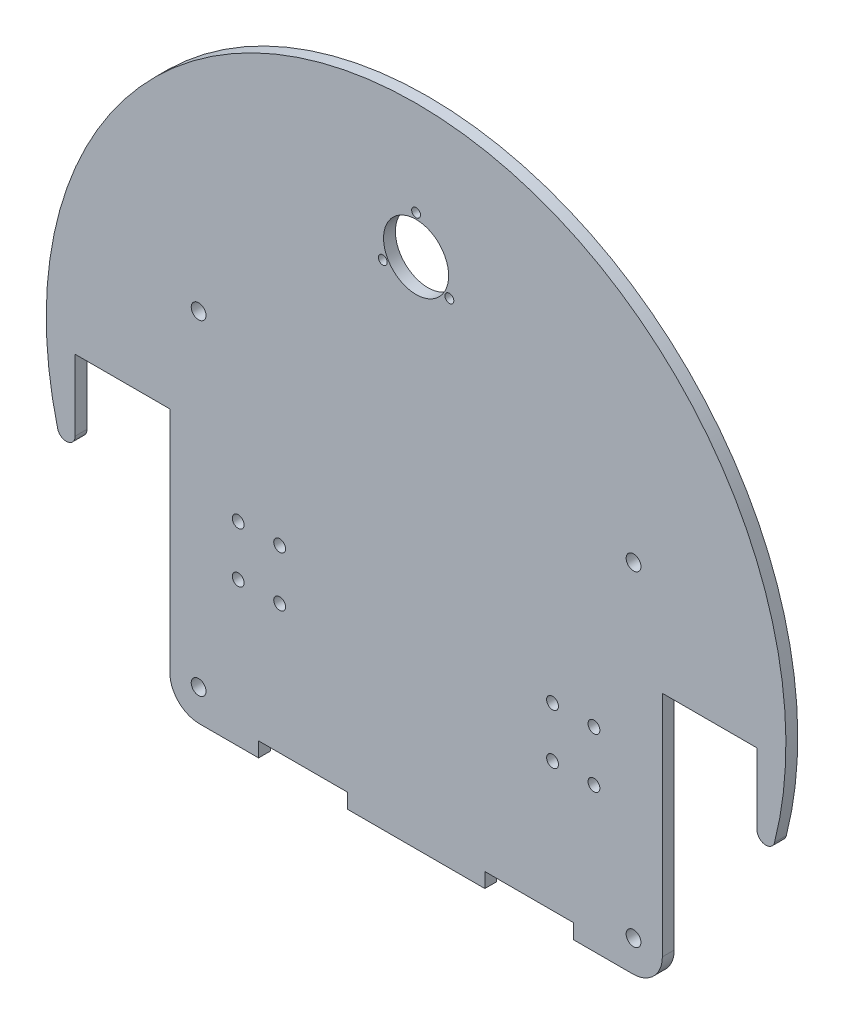
SolidWorks part; units mm, degrees
ref_plane "Front Plane" through (0, 0, 0) normal (0, 0, 1) x (1, 0, 0)
ref_plane "Top Plane" through (0, 0, 0) normal (0, 1, 0) x (1, 0, 0)
ref_plane "Right Plane" through (0, 0, 0) normal (1, 0, 0) x (0, 0, -1)
sketch "Sketch1" plane through (0, 0, 0) normal (0, 0, 1) x (1, 0, 0)
  line L0 (-115.2338, -48.4373) -> (-115.2338, -6.094)
  line L1 (-115.2338, -6.094) -> (-83.2338, -6.094)
  line L2 (-83.2338, -6.094) -> (-83.2338, -93.2584)
  line L3 (0, 125) -> (0, -125) construction
  line L4 (115.2338, -48.4373) -> (115.2338, -6.094)
  line L5 (115.2338, -6.094) -> (83.2338, -6.094)
  line L6 (83.2338, -6.094) -> (83.2338, -93.2584)
  arc A0 (-83.2338, -93.2584) -> (83.2338, -93.2584) centre (0, 0) ccw
  circle A1 centre (0, 80) radius 11
  arc A2 (115.2338, -48.4373) -> (-115.2338, -48.4373) centre (0, 0) ccw
  dimension "D1" = 250
  dimension "D2" = 22
  dimension "D3" = 80
  dimension "D4" = 32
extrude "Boss-Extrude1" add sketch "Sketch1" along normal blind 4
sketch "Sketch2" plane through (0, 0, 4) normal (0, 0, 1) x (1, 0, 0)
  circle A0 centre (0, 92.9904) radius 1.5
  circle A1 centre (11.25, 73.5048) radius 1.5
  circle A2 centre (-11.25, 73.5048) radius 1.5
  dimension "D1" = 3
extrude "Cut-Extrude1" cut sketch "Sketch2" against normal blind 10
sketch "Sketch3" plane through (0, 0, 4) normal (0, 0, 1) x (1, 0, 0)
  line L0 (-83.2338, -93.2584) -> (83.2338, -93.2584)
  arc A0 (-83.2338, -93.2584) -> (83.2338, -93.2584) centre (0, 0) ccw construction
  arc A1 (-83.2338, -93.2584) -> (83.2338, -93.2584) centre (0, 0) ccw
extrude "Cut-Extrude2" cut sketch "Sketch3" against normal blind 10
fillet "Fillet1" radius 10 2 edges at (-83.2338, -93.2584, 2) (83.2338, -93.2584, 2)
fillet "Fillet3" radius 3 2 edges at (115.2338, -48.4373, 2) (-115.2338, -48.4373, 2)
sketch "Sketch5" plane through (0, 0, 4) normal (0, 0, 1) x (1, 0, 0)
  line L0 (73.2338, -93.2584) -> (-73.2338, -93.2584) construction
  line L1 (53.2338, -93.2584) -> (23.2338, -93.2584)
  line L2 (53.2338, -93.2584) -> (53.2338, -88.2584)
  line L3 (53.2338, -88.2584) -> (23.2338, -88.2584)
  line L4 (23.2338, -93.2584) -> (23.2338, -88.2584)
  line L5 (83.2338, -83.2584) -> (83.2338, -6.094) construction
  line L6 (0, 0) -> (0, -93.2584) construction
  line L7 (-23.2338, -93.2584) -> (-23.2338, -88.2584)
  line L8 (-53.2338, -88.2584) -> (-23.2338, -88.2584)
  line L9 (-53.2338, -93.2584) -> (-53.2338, -88.2584)
  line L10 (-53.2338, -93.2584) -> (-23.2338, -93.2584)
  dimension "D1" = 30
  dimension "D2" = 5
  dimension "D3" = 30
extrude "Cut-Extrude4" cut sketch "Sketch5" against normal blind 10
sketch "Sketch6" plane through (0, 0, 4) normal (0, 0, 1) x (1, 0, 0)
  circle A0 centre (-73.5, -82.6455) radius 2.5
  circle A1 centre (73.5, -82.6455) radius 2.5
  circle A2 centre (73.5, 27.3545) radius 2.5
  circle A3 centre (-73.5, 27.3545) radius 2.5
  dimension "D1" = 5
extrude "Cut-Extrude5" cut sketch "Sketch6" against normal through all
sketch "Sketch7" plane through (0, 0, 4) normal (0, 0, 1) x (1, 0, 0)
  line L0 (-115.2338, -30.0794) -> (-115.2338, 48.4373)
  arc A0 (121.1412, -30.819) -> (-121.1412, -30.819) centre (0, 0) ccw construction
  arc A1 (-121.1412, -30.819) -> (-115.2338, -30.0794) centre (-118.2338, -30.0794) ccw construction
  arc A2 (-115.2338, 48.4373) -> (-121.1412, -30.819) centre (0, 0) ccw
  arc A3 (-121.1412, -30.819) -> (-115.2338, -30.0794) centre (-118.2338, -30.0794) ccw
extrude "Cut-Extrude6" [suppressed] cut sketch "Sketch7" against normal blind 10
mirror "Mirror1" [suppressed] about plane through (0, 0, 0) normal (1, 0, 0)
sketch "Sketch8" plane through (0, 0, 4) normal (0, 0, 1) x (1, 0, 0)
  circle A0 centre (46.1155, -27.4976) radius 2
  circle A1 centre (46.1155, -44.4976) radius 2
  circle A2 centre (60.1155, -44.4976) radius 2
  circle A3 centre (60.1155, -27.4976) radius 2
  dimension "D1" = 4
extrude "Cut-Extrude7" cut sketch "Sketch8" against normal through all
ref_plane "Plane1" through (0, 0, 0) normal (-1, 0, 0) x (0, 0, 1)
mirror "Mirror2" about plane through (0, 0, 0) normal (-1, 0, 0) of "Cut-Extrude7"
